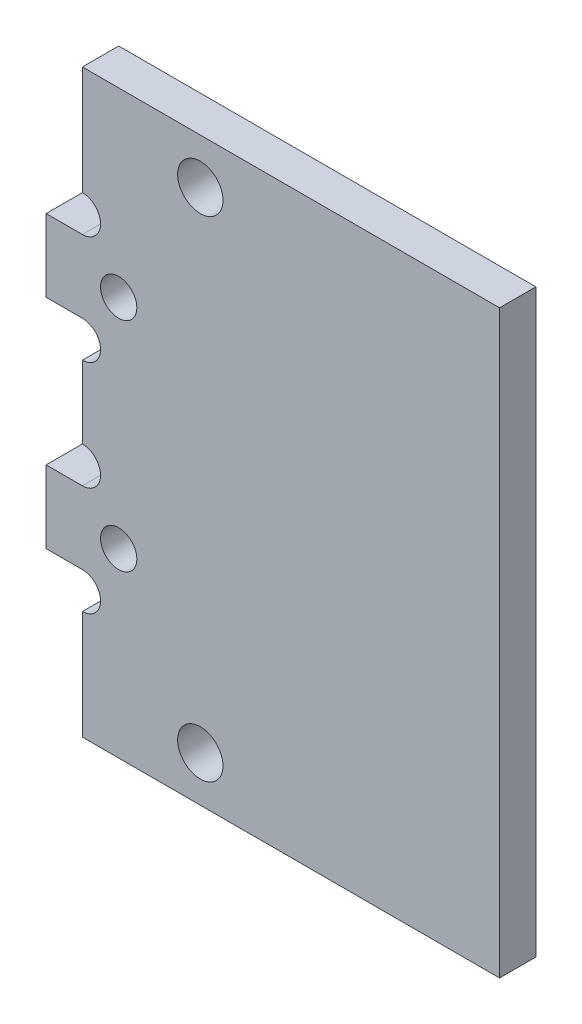
SolidWorks part; units mm, degrees
material "自訂玻璃纖維"
ref_plane "前基準面" through (0, 0, 0) normal (0, 0, 1) x (1, 0, 0)
ref_plane "上基準面" through (0, 0, 0) normal (0, 1, 0) x (1, 0, 0)
ref_plane "右基準面" through (0, 0, 0) normal (1, 0, 0) x (0, 0, -1)
sketch "草圖1" plane through (0, 0, 0) normal (0, 0, 1) x (1, 0, 0)
  line L0 (-17.2162, 10.1625) -> (13.2838, 10.1625)
  line L1 (13.2838, 10.1625) -> (13.2838, -21.8375)
  line L2 (13.2838, -21.8375) -> (-17.2162, -21.8375)
  line L3 (-25.7162, 2.1625) -> (-27.7162, 2.1625)
  line L4 (-27.7162, 2.1625) -> (-27.7162, -1.8375)
  line L5 (-17.2162, 10.1625) -> (-21.7162, 10.1625)
  line L6 (-27.7162, -1.8375) -> (-25.7162, -1.8375)
  line L7 (-17.2162, -21.8375) -> (-19.7162, -21.8375)
  line L8 (-25.7162, -3.8375) -> (-25.7162, -7.8375)
  line L9 (-21.7162, 10.1625) -> (-25.7162, 10.1625)
  line L10 (-25.7162, -15.8375) -> (-25.7162, -21.8375)
  line L11 (-19.7162, -21.8375) -> (-25.7162, -21.8375)
  line L12 (-25.7162, 10.1625) -> (-25.7162, 4.1625)
  line L13 (-27.7162, -9.8375) -> (-25.7162, -9.8375)
  line L14 (-27.7162, -13.8375) -> (-27.7162, -9.8375)
  line L15 (-25.7162, -13.8375) -> (-27.7162, -13.8375)
  circle A0 centre (-19.2162, 7.6625) radius 1.25
  circle A1 centre (-19.2162, -19.3375) radius 1.25
  circle A2 centre (10.7838, -19.3375) radius 1.25
  circle A3 centre (10.7838, 7.6625) radius 1.25
  arc A4 (-25.7162, 2.1625) -> (-25.7162, 4.1625) centre (-25.7162, 3.1625) ccw
  circle A5 centre (-23.7162, 0.1625) radius 1
  circle A6 centre (-23.7162, -11.8375) radius 1
  arc A7 (-25.7162, -1.8375) -> (-25.7162, -3.8375) centre (-25.7162, -2.8375) cw
  arc A8 (-25.7162, -9.8375) -> (-25.7162, -7.8375) centre (-25.7162, -8.8375) ccw
  arc A9 (-25.7162, -13.8375) -> (-25.7162, -15.8375) centre (-25.7162, -14.8375) cw
  dimension "D7" = 2
  dimension "D8" = 2
  dimension "D9" = 30
  dimension "D4" = 2.5
  dimension "D5" = 30
  dimension "D2" = 2.5
  dimension "D3" = 35
  dimension "D6" = 4
  dimension "D11" = 4
extrude "填料-伸長1" add sketch "草圖1" along normal blind 2
sketch "草圖4" plane through (0, 0, 0) normal (0, 0, -1) x (-1, 0, 0)
  line L0 (-13.2838, 5.1625) -> (2.7162, 5.1625)
  line L1 (-13.2838, -21.8375) -> (-13.2838, 10.1625) construction
  line L2 (2.7162, 5.1625) -> (2.7162, -16.8375)
  line L3 (2.7162, -16.8375) -> (-13.2838, -16.8375)
  line L4 (-13.2838, -16.8375) -> (-13.2838, 5.1625)
  circle A0 centre (-10.7838, 7.6625) radius 1.25 construction
  circle A1 centre (-10.7838, -19.3375) radius 1.25 construction
  dimension "D1" = 2.5
  dimension "D2" = 2.5
  dimension "D3" = 16
extrude "除料-伸長1" cut sketch "草圖4" against normal blind 2
fillet "圓角2" radius 2.5 2 edges at (13.2838, -16.8375, 1) (13.2838, 5.1625, 1)
fillet "圓角3" radius 5 2 edges at (-2.7162, -16.8375, 1) (-2.7162, 5.1625, 1)
sketch "草圖6" plane through (0, 0, 0) normal (0, 0, -1) x (-1, 0, 0)
  line L0 (-13.2838, 10.1625) -> (25.7162, 10.1625) construction
  line L1 (2.7162, 10.1625) -> (-13.2838, 10.1625)
  line L2 (2.7162, 10.1625) -> (2.7162, -21.8375)
  line L3 (2.7162, -21.8375) -> (-13.2838, -21.8375)
  line L4 (-13.2838, 10.1625) -> (-13.2838, -21.8375)
extrude "除料-伸長3" cut sketch "草圖6" against normal blind 10
